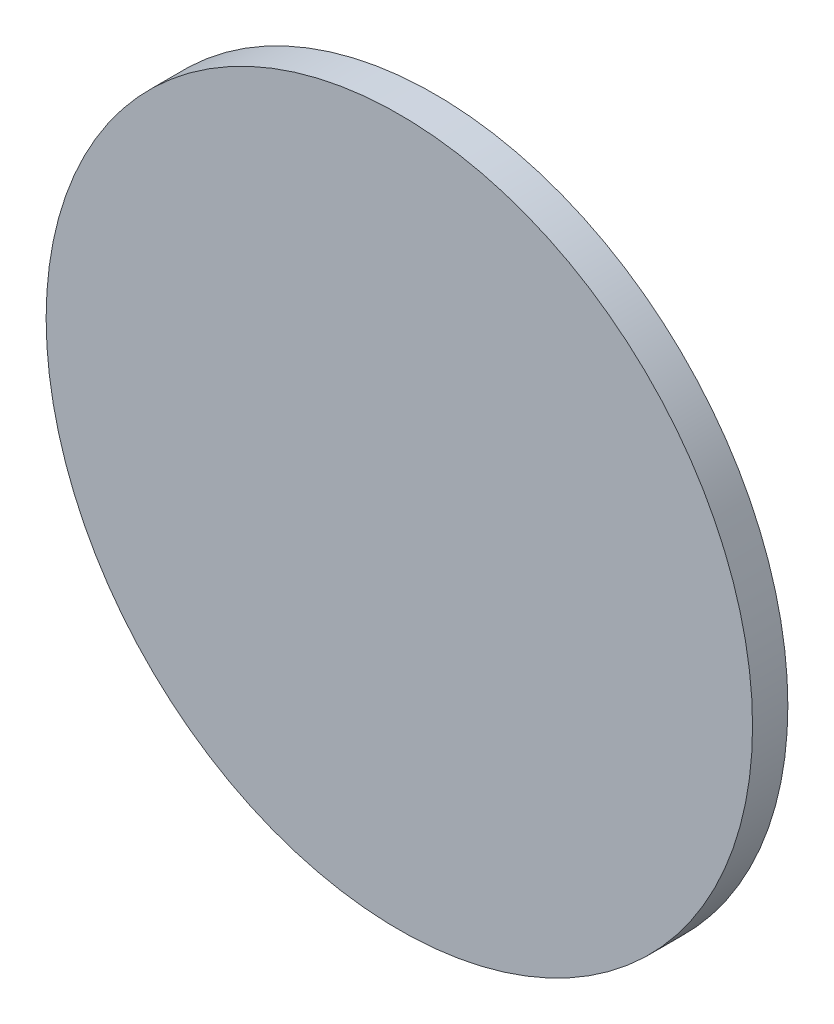
SolidWorks part; units mm, degrees
ref_plane "Front Plane" through (0, 0, 0) normal (0, 0, 1) x (1, 0, 0)
ref_plane "Top Plane" through (0, 0, 0) normal (0, 1, 0) x (1, 0, 0)
ref_plane "Right Plane" through (0, 0, 0) normal (1, 0, 0) x (0, 0, -1)
sketch "Sketch1" plane through (0, 0, 0) normal (0, 0, 1) x (1, 0, 0)
  circle A0 centre (0, 0) radius 50
  dimension "D1" = 100
extrude "Boss-Extrude1" add sketch "Sketch1" along normal blind 5
sketch "Sketch2" plane through (0, 0, 0) normal (0, 0, -1) x (-1, 0, 0)
  line L1 (-17, -35) -> (17, -35)
  line L2 (-17, -35) -> (-17, 35)
  line L3 (-17, 35) -> (17, 35)
  line L4 (17, -35) -> (17, 35)
  line L5 (-17, -35) -> (17, 35) construction
  line L6 (-17, 35) -> (17, -35) construction
  point P0 (0, 0)
  dimension "D1" = 70
  dimension "D2" = 34
extrude "Boss-Extrude3" add sketch "Sketch2" along normal blind 8
sketch "Sketch3" plane through (0, 0, -8) normal (0, 0, -1) x (-1, 0, 0)
  line L1 (-13.5, -31.5) -> (13.5, -31.5)
  line L2 (-13.5, -31.5) -> (-13.5, 31.5)
  line L3 (-13.5, 31.5) -> (13.5, 31.5)
  line L4 (13.5, -31.5) -> (13.5, 31.5)
  line L5 (-13.5, -31.5) -> (13.5, 31.5) construction
  line L6 (-13.5, 31.5) -> (13.5, -31.5) construction
  point P0 (0, 0)
  dimension "D1" = 63
  dimension "D2" = 27
extrude "Cut-Extrude1" cut sketch "Sketch3" against normal blind 8
sketch "Sketch4" plane through (0, -35, 0) normal (0, -1, 0) x (1, 0, 0)
  line L0 (-17, -8) -> (-17, 0) construction
  line L1 (-12, -2) -> (-8, -2)
  line L2 (-12, -2) -> (-12, -6)
  line L3 (-12, -6) -> (-8, -6)
  line L4 (-8, -2) -> (-8, -6)
  line L5 (17, 0) -> (-17, 0) construction
  dimension "D1" = 4
  dimension "D2" = 5
  dimension "D3" = 4
  dimension "D4" = 2
extrude "Cut-Extrude2" cut sketch "Sketch4" against normal through all
pattern_linear "LPattern1" count 3 spacing 10 along (1, 0, 0) of "Cut-Extrude2"
sketch "Sketch5" plane through (-17, 0, 0) normal (-1, 0, 0) x (0, 0, 1)
  line L0 (0, -35) -> (0, 35) construction
  line L1 (-6, 30) -> (-2, 30)
  line L2 (-6, 30) -> (-6, 26)
  line L3 (-6, 26) -> (-2, 26)
  line L4 (-2, 30) -> (-2, 26)
  line L5 (-8, 35) -> (0, 35) construction
  dimension "D1" = 4
  dimension "D2" = 4
  dimension "D3" = 2
  dimension "D4" = 5
extrude "Cut-Extrude3" cut sketch "Sketch5" against normal through all
pattern_linear "LPattern2" count 8 spacing 8 along (0, -1, 0) of "Cut-Extrude3"
